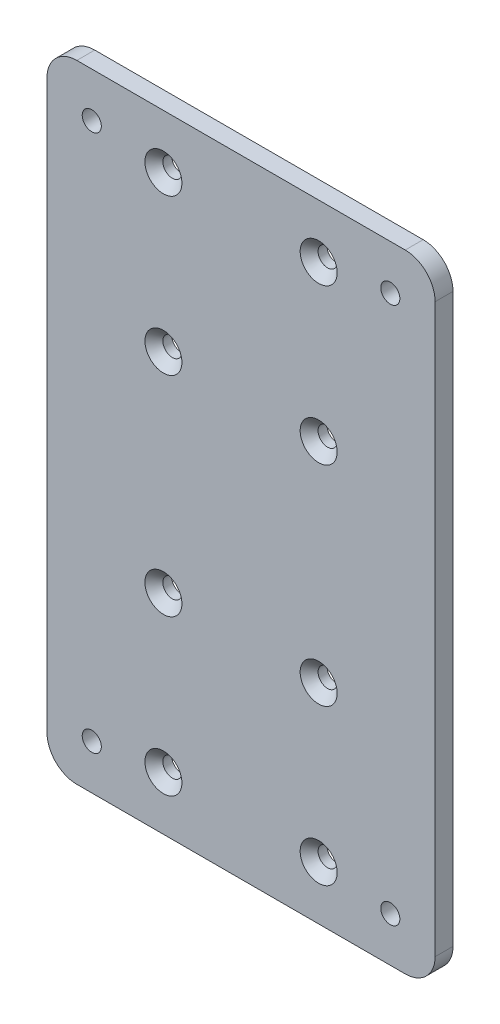
SolidWorks part; units mm, degrees
ref_plane "正面" through (0, 0, 0) normal (0, 0, 1) x (1, 0, 0)
ref_plane "平面" through (0, 0, 0) normal (0, 1, 0) x (1, 0, 0)
ref_plane "右側面" through (0, 0, 0) normal (1, 0, 0) x (0, 0, -1)
sketch "ｽｹｯﾁ2" plane through (0, 0, 0) normal (0, 0, 1) x (1, 0, 0)
  line L0 (0, -30.5) -> (0, 30.5) construction
  line L1 (-32.5, -52.5) -> (32.5, -52.5)
  line L2 (-32.5, -52.5) -> (-32.5, 52.5)
  line L3 (-32.5, 52.5) -> (32.5, 52.5)
  line L4 (32.5, -52.5) -> (32.5, 52.5)
  line L5 (-32.5, -52.5) -> (32.5, 52.5) construction
  line L6 (-32.5, 52.5) -> (32.5, -52.5) construction
  line L7 (-13, 43.5) -> (13, 17.5) construction
  line L8 (13, 43.5) -> (-13, 17.5) construction
  line L9 (-13, -43.5) -> (13, -17.5) construction
  line L10 (13, -43.5) -> (-13, -17.5) construction
  line L12 (-25, -45) -> (25, -45) construction
  line L13 (-25, -45) -> (-25, 45) construction
  line L14 (-25, 45) -> (25, 45) construction
  line L15 (25, -45) -> (25, 45) construction
  line L16 (-25, -45) -> (25, 45) construction
  line L17 (-25, 45) -> (25, -45) construction
  circle A0 centre (-13, 43.5) radius 1.6
  circle A1 centre (13, 17.5) radius 1.6
  circle A2 centre (13, 43.5) radius 1.6
  circle A3 centre (-13, 17.5) radius 1.6
  circle A4 centre (-13, -17.5) radius 1.6
  circle A5 centre (13, -17.5) radius 1.6
  circle A6 centre (-13, -43.5) radius 1.6
  circle A7 centre (13, -43.5) radius 1.6
  circle A8 centre (-25, 45) radius 1.6
  circle A9 centre (25, 45) radius 1.6
  circle A10 centre (25, -45) radius 1.6
  circle A11 centre (-25, -45) radius 1.6
  point P0 (0, 0)
  point P9 (0, 0)
  point P12 (0, 30.5)
  point P15 (0, 30.5)
  point P18 (0, -30.5)
  point P21 (0, -30.5)
  point P30 (0, 0)
  dimension "D1" = 3.2
  dimension "D2" = 26
  dimension "D3" = 3.2
  dimension "D4" = 7.5
  dimension "D8" = 35
  dimension "D5" = 7.5
  dimension "D6" = 90
  dimension "D7" = 50
  dimension "D9" = 45
extrude "ﾎﾞｽ - 押し出し1" add sketch "ｽｹｯﾁ2" along normal blind 3
fillet "ﾌｨﾚｯﾄ1" radius 5 4 edges at (-32.5, -52.5, 1.5) (32.5, -52.5, 1.5) (-32.5, 52.5, 1.5) (32.5, 52.5, 1.5)
chamfer "面取り1" distance 1.5 angle 45 8 edges at (-11.4, -43.5, 3) (14.6, -43.5, 3) (14.6, -17.5, 3) (-11.4, -17.5, 3) (14.6, 17.5, 3) (-11.4, 17.5, 3) (14.6, 43.5, 3) (-11.4, 43.5, 3)
